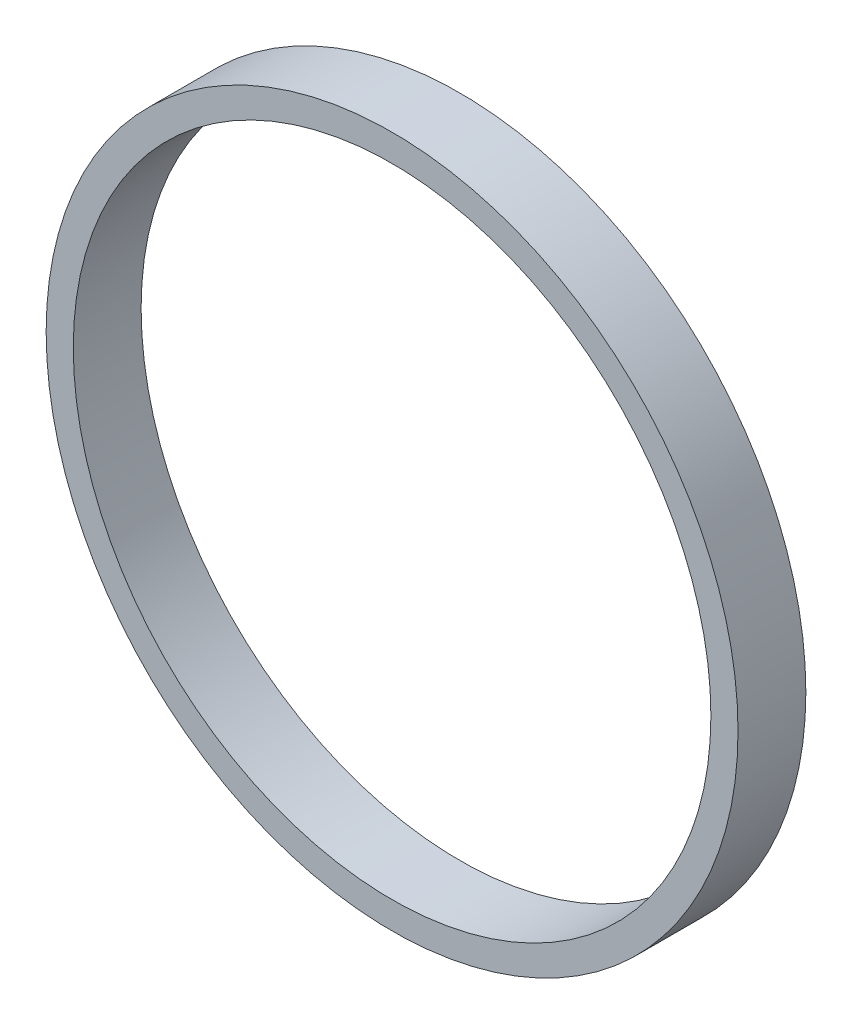
SolidWorks part; units mm, degrees
ref_plane "Front Plane" through (0, 0, 0) normal (0, 0, 1) x (1, 0, 0)
ref_plane "Top Plane" through (0, 0, 0) normal (0, 1, 0) x (1, 0, 0)
ref_plane "Right Plane" through (0, 0, 0) normal (1, 0, 0) x (0, 0, -1)
sketch "草圖1" plane through (0, 0, 0) normal (0, 0, 1) x (1, 0, 0)
  circle A0 centre (0, 0) radius 51
  circle A1 centre (0, 0) radius 47
extrude "填料-伸長1" add sketch "草圖1" along normal blind 10 from offset 267.5
